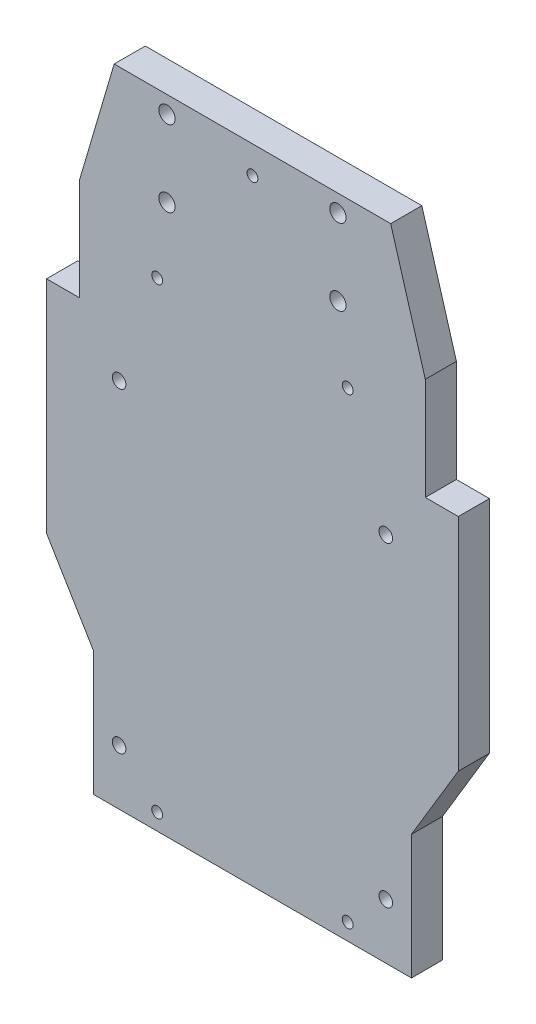
SolidWorks part; units mm, degrees
ref_plane "Front Plane" through (0, 0, 0) normal (0, 0, 1) x (1, 0, 0)
ref_plane "Top Plane" through (0, 0, 0) normal (0, 1, 0) x (1, 0, 0)
ref_plane "Right Plane" through (0, 0, 0) normal (1, 0, 0) x (0, 0, -1)
sketch "Sketch1" plane through (0, 0, 0) normal (0, 0, 1) x (1, 0, 0)
  line L0 (0, 63.5) -> (0, 0) construction
  line L2 (-37.8206, -20.2565) -> (-37.8206, 20.2565)
  line L3 (-37.8206, 20.2565) -> (-31.75, 20.2565)
  line L4 (37.8206, -20.2565) -> (37.8206, 20.2565)
  line L5 (-31.75, 20.2565) -> (31.75, 20.2565) construction
  line L6 (-37.8206, -20.2565) -> (37.8206, 20.2565) construction
  line L7 (-25.4, 60.6425) -> (25.4, 60.6425)
  line L8 (-31.75, 39.0525) -> (-31.75, 20.2565)
  line L10 (31.75, 39.0525) -> (31.75, 20.2565)
  line L12 (-29.21, -57.4675) -> (29.21, -57.4675)
  line L13 (31.75, 20.2565) -> (37.8206, 20.2565)
  line L14 (-31.75, 39.0525) -> (-25.4, 60.6425)
  line L15 (31.75, 39.0525) -> (25.4, 60.6425)
  line L16 (-31.75, 39.0525) -> (31.75, 39.0525) construction
  line L17 (-29.21, -57.4675) -> (-29.21, -34.6075)
  line L19 (29.21, -57.4675) -> (29.21, -34.6075)
  line L20 (-29.21, -57.4675) -> (29.21, -34.6075) construction
  line L21 (-29.21, -34.6075) -> (29.21, -57.4675) construction
  line L22 (-29.21, -34.6075) -> (-37.8206, -20.2565)
  line L23 (29.21, -34.6075) -> (37.8206, -20.2565)
  line L24 (-37.8206, -20.2565) -> (37.8206, -20.2565) construction
  line L25 (-37.8206, 20.2565) -> (37.8206, -20.2565) construction
  point P0 (0, 0)
  point P4 (0, -20.2565)
  point P6 (0, -46.0375)
  point P19 (0, 60.6425)
  dimension "D1" = 75.6412
  dimension "D2" = 54.864
  dimension "D3" = 63.5
  dimension "D4" = 40.386
  dimension "D5" = 18.796
  dimension "D6" = 6.35
  dimension "D7" = 6.35
  dimension "D8" = 22.86
  dimension "D9" = 58.42
  dimension "D10" = 14.351
  dimension "D11" = 40.513
extrude "Boss-Extrude1" add sketch "Sketch1" along normal blind 5.715
ref_plane "Plane1" through (0, 0, 2.8575) normal (0, 0, -1) x (-1, 0, 0)
sketch "Sketch2" plane through (0, 0, 2.8575) normal (0, 0, -1) x (-1, 0, 0)
  line L0 (0, 0) -> (0, 43.6603) construction
  line L1 (-60.6002, -34.6075) -> (60.6002, -34.6075) construction
sketch "Sketch3" plane through (0, 0, 5.715) normal (0, 0, 1) x (1, 0, 0)
  line L0 (-24.5, 10.6925) -> (24.5, 10.6925) construction
  line L1 (0, -200000) -> (0, 200043.6603) construction
  line L2 (-24.5, 10.6925) -> (-24.5, -47.3075) construction
  line L3 (-24.5, -47.3075) -> (24.5, -47.3075) construction
  line L4 (24.5, -47.3075) -> (24.5, 10.6925) construction
  line L6 (25.4, 60.6425) -> (-25.4, 60.6425) construction
  line L7 (-17.5, -54.4375) -> (17.5, -54.4375) construction
  line L8 (25.4, 60.6425) -> (-25.4, 60.6425) construction
  line L9 (15.7, 57.4825) -> (-15.7, 57.4825) construction
  line L10 (-17.5, 30.5625) -> (17.5, 30.5625) construction
  line L12 (15.7, 57.4825) -> (15.7, 43.4825) construction
  line L13 (15.7, 43.4825) -> (-15.7, 43.4825) construction
  line L14 (-15.7, 43.4825) -> (-15.7, 57.4825) construction
  line L15 (0, 0) -> (0, -27.5534) construction
  circle A0 centre (-24.5, 10.6925) radius 1.25
  circle A1 centre (24.5, 10.6925) radius 1.25
  circle A2 centre (-24.5, -47.3075) radius 1.25
  circle A3 centre (24.5, -47.3075) radius 1.25
  circle A4 centre (0, 55.5625) radius 1
  circle A5 centre (17.5, 30.5625) radius 1
  circle A6 centre (-17.5, 30.5625) radius 1
  circle A8 centre (-17.5, -54.4375) radius 1
  circle A9 centre (17.5, -54.4375) radius 1
  circle A10 centre (-15.7, 57.4825) radius 1.5
  circle A11 centre (15.7, 57.4825) radius 1.5
  circle A12 centre (15.7, 43.4825) radius 1.5
  circle A13 centre (-15.7, 43.4825) radius 1.5
  point P4 (0, 10.6925)
  point P23 (0, 30.5625)
  point P27 (0, -54.4375)
  point P36 (0, 57.4825)
  dimension "D1" = 2.5
  dimension "D5" = 2
  dimension "D11" = 85
  dimension "D9" = 3
  dimension "D12" = 3.16
  dimension "D2" = 49
  dimension "D3" = 58
  dimension "D4" = 10.16
  dimension "D6" = 5.08
  dimension "D7" = 35
  dimension "D8" = 110
  dimension "D10" = 35
  dimension "D13" = 14
  dimension "D14" = 31.4
extrude "Cut-Extrude1" cut sketch "Sketch3" against normal up to surface (5.715 mm away) up to face at (0, 3.9824, 0)
